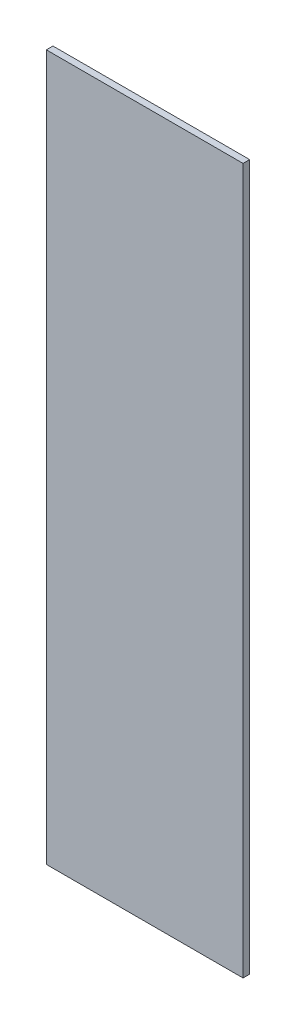
SolidWorks part; units mm, degrees
ref_plane "Спереди" through (0, 0, 0) normal (0, 0, 1) x (1, 0, 0)
ref_plane "Сверху" through (0, 0, 0) normal (0, 1, 0) x (1, 0, 0)
ref_plane "Справа" through (0, 0, 0) normal (1, 0, 0) x (0, 0, -1)
sketch "Эскиз1" plane through (0, 0, 0) normal (0, 1, 0) x (1, 0, 0)
  line L1 (0, 0) -> (148.63, 0)
  line L2 (0, 0) -> (0, -5)
  line L3 (0, -5) -> (148.63, -5)
  line L4 (148.63, 0) -> (148.63, -5)
extrude "Вытянуть1" add sketch "Эскиз1" along normal blind 533
